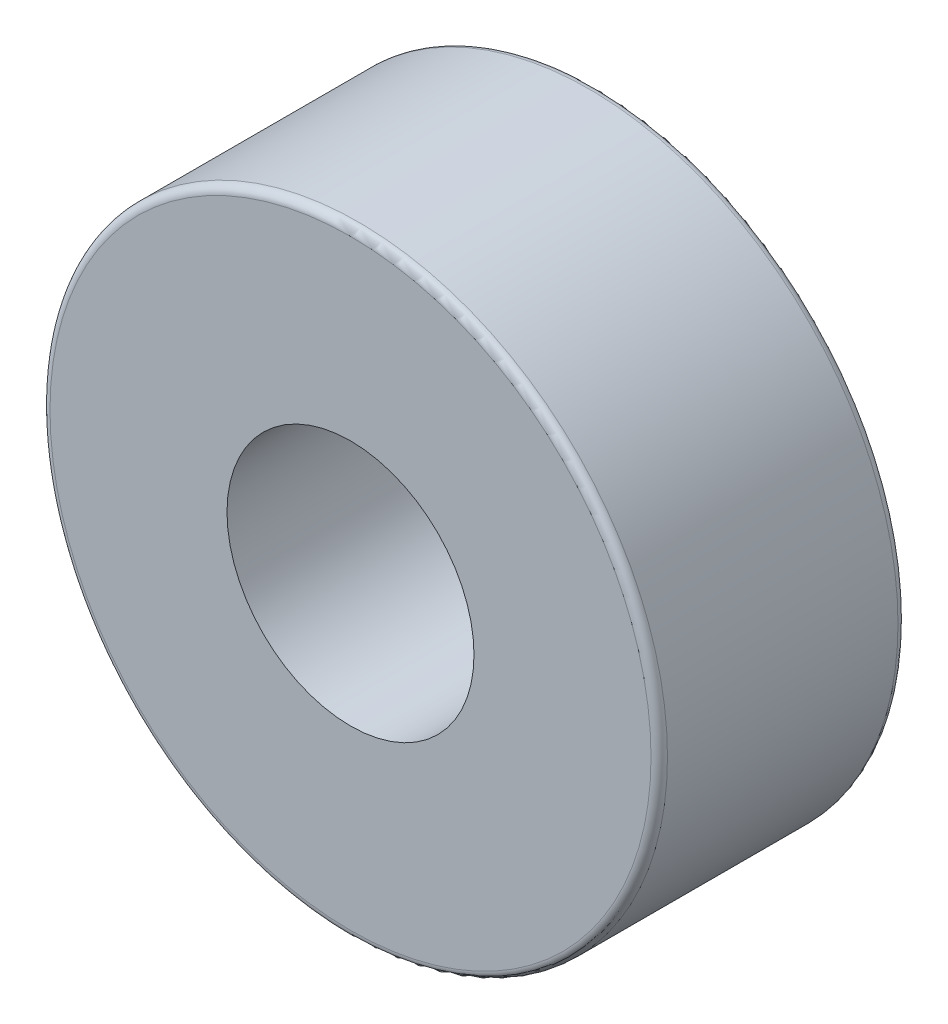
SolidWorks part; units mm, degrees
ref_plane "Front Plane" through (0, 0, 0) normal (0, 0, 1) x (1, 0, 0)
ref_plane "Top Plane" through (0, 0, 0) normal (0, 1, 0) x (1, 0, 0)
ref_plane "Right Plane" through (0, 0, 0) normal (1, 0, 0) x (0, 0, -1)
sketch "Sketch1" plane through (0, 0, 0) normal (0, 0, 1) x (1, 0, 0)
  circle A0 centre (0, 0) radius 7.5
  circle A1 centre (0, 0) radius 3
  dimension "D1" = 15
  dimension "D2" = 6
extrude "Boss-Extrude1" add sketch "Sketch1" along normal blind 6 contours A0
sketch "Sketch2" plane through (0, 0, 0) normal (0, 0, 1) x (1, 0, 0)
  circle A0 centre (0, 0) radius 3
  dimension "D1" = 6
extrude "Cut-Extrude1" cut sketch "Sketch2" along normal up to surface (6 mm away) contours A0 up to face at (7.5, 0, 6)
fillet "Fillet1" radius 0.2 2 edges at (7.5, 0, 0) (7.5, 0, 6)
